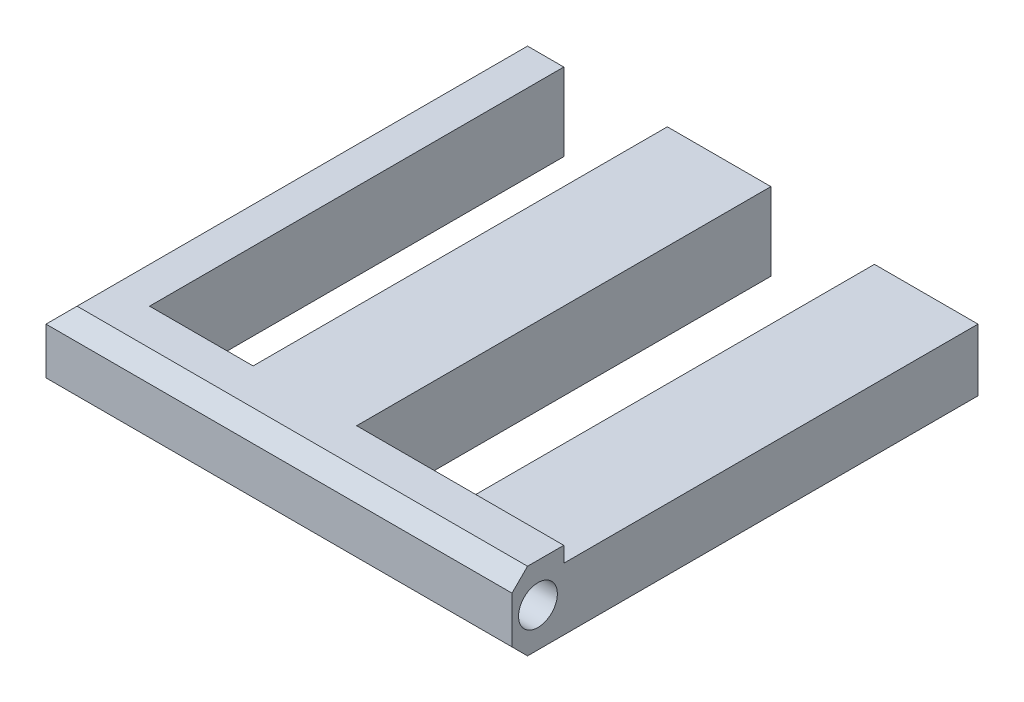
SolidWorks part; units mm, degrees
ref_plane "Front Plane" through (0, 0, 0) normal (0, 0, 1) x (1, 0, 0)
ref_plane "Top Plane" through (0, 0, 0) normal (0, 1, 0) x (1, 0, 0)
ref_plane "Right Plane" through (0, 0, 0) normal (1, 0, 0) x (0, 0, -1)
sketch "Sketch1" plane through (0, 0, 0) normal (0, 1, 0) x (1, 0, 0)
  line L0 (0, 25.4) -> (-203.2, 25.4)
  line L1 (0, 0) -> (-228.6, 0)
  line L2 (0, 0) -> (0, 228.6)
  line L3 (0, 228.6) -> (-228.6, 228.6)
  line L4 (-228.6, 0) -> (-228.6, 228.6)
  line L5 (-203.2, 25.4) -> (-203.2, 228.6)
  line L6 (-152.4, 25.4) -> (-152.4, 228.6)
  line L7 (-101.6, 25.4) -> (-101.6, 228.6)
  line L8 (-50.8, 25.4) -> (-50.8, 228.6)
  dimension "D1" = 228.6
  dimension "D2" = 228.6
  dimension "D3" = 25.4
  dimension "D4" = 50.8
  dimension "D5" = 50.8
  dimension "D6" = 50.8
extrude "Boss-Extrude2" add sketch "Sketch1" along normal blind 38.1 contours L0 L5 L3 L4 L1 L2 | L0 L7 L3 L6 | L8 L0 L2 L3
sketch "Sketch2" plane through (0, 0, -228.6) normal (0, 0, -1) x (-1, 0, 0)
  circle A0 centre (215.9, 19.05) radius 9.525
  dimension "D1" = 19.05
extrude "Cut-Extrude1" cut sketch "Sketch2" against normal blind 38.1
sketch "Sketch3" plane through (0, 0, 0) normal (1, 0, 0) x (0, 0, -1)
  circle A0 centre (12.729, 19.05) radius 9.525
  dimension "D1" = 19.05
extrude "Cut-Extrude2" cut sketch "Sketch3" against normal blind 38.1
sketch "Sketch4" plane through (0, 38.1, 0) normal (0, 1, 0) x (1, 0, 0)
  line L0 (-50.8, 25.4) -> (-101.6, 25.4) construction
  line L1 (177.8, 279.429) -> (-76.2, 279.429)
  line L2 (177.8, 279.429) -> (177.8, 25.4)
  line L3 (177.8, 25.4) -> (-76.2, 25.4)
  line L4 (-76.2, 279.429) -> (-76.2, 25.4)
extrude "Cut-Extrude3" cut sketch "Sketch4" against normal blind 7.62
chamfer "Chamfer1" distance 7.62 angle 45 4 edges at (-114.3, 0, 0) (-114.3, 38.1, 0) (-228.6, 0, -114.3) (-228.6, 38.1, -114.3)
